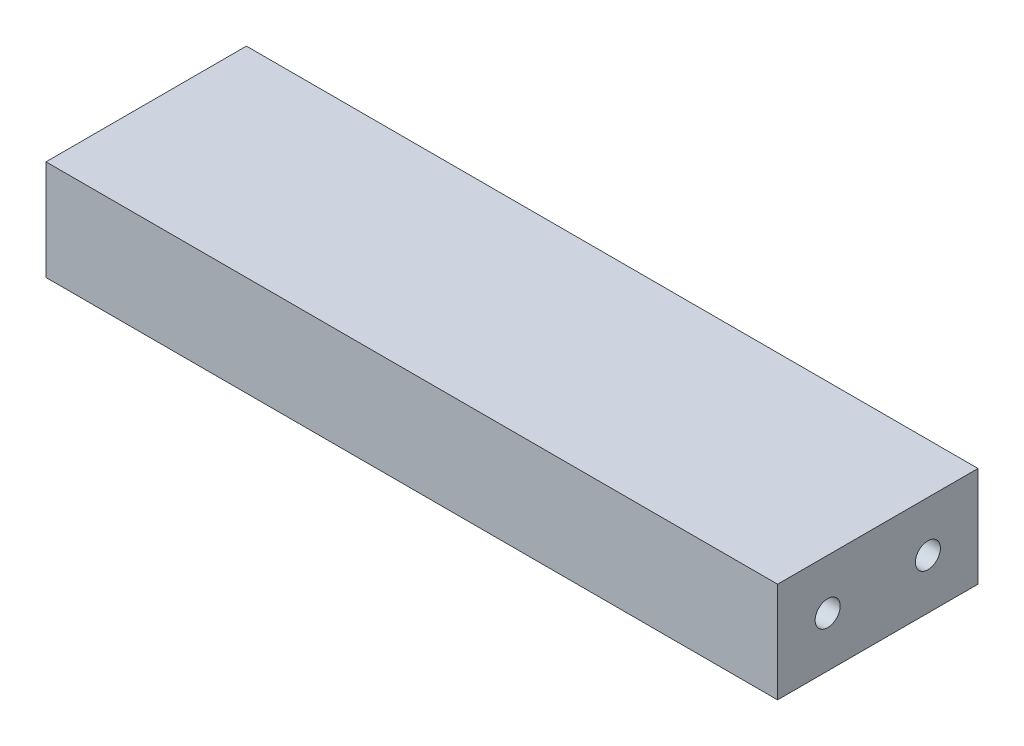
SolidWorks part; units mm, degrees
ref_plane "Front" through (0, 0, 0) normal (0, 0, 1) x (1, 0, 0)
ref_plane "Top" through (0, 0, 0) normal (0, 1, 0) x (1, 0, 0)
ref_plane "Right" through (0, 0, 0) normal (1, 0, 0) x (0, 0, -1)
sketch "草图1" plane through (0, 0, 0) normal (0, 1, 0) x (1, 0, 0)
  line L1 (36.5, -10) -> (-36.5, -10)
  line L2 (36.5, -10) -> (36.5, 10)
  line L3 (36.5, 10) -> (-36.5, 10)
  line L4 (-36.5, -10) -> (-36.5, 10)
  line L5 (36.5, -10) -> (-36.5, 10) construction
  line L6 (36.5, 10) -> (-36.5, -10) construction
  point P0 (0, 0)
  dimension "D1" = 73
  dimension "D2" = 20
extrude "凸台-拉伸1" add sketch "草图1" along normal blind 10
sketch "草图2" plane through (36.5, 0, 0) normal (1, 0, 0) x (0, 0, -1)
  line L0 (-10, 5) -> (10, 5) construction
  line L1 (-10, 10) -> (-10, 0) construction
  line L2 (10, 10) -> (10, 0) construction
  line L3 (0, 10) -> (0, 0) construction
  line L4 (-10, 10) -> (10, 10) construction
  line L5 (-10, 0) -> (10, 0) construction
  circle A0 centre (-5, 5) radius 1.25
  circle A1 centre (5, 5) radius 1.25
  point P16 (0, 0)
  dimension "D1" = 2.5
  dimension "D2" = 2.5
  dimension "D3" = 10
extrude "切除-拉伸1" cut sketch "草图2" against normal blind 20
mirror "镜向1" about plane through (0, 0, 0) normal (1, 0, 0) of "切除-拉伸1"
